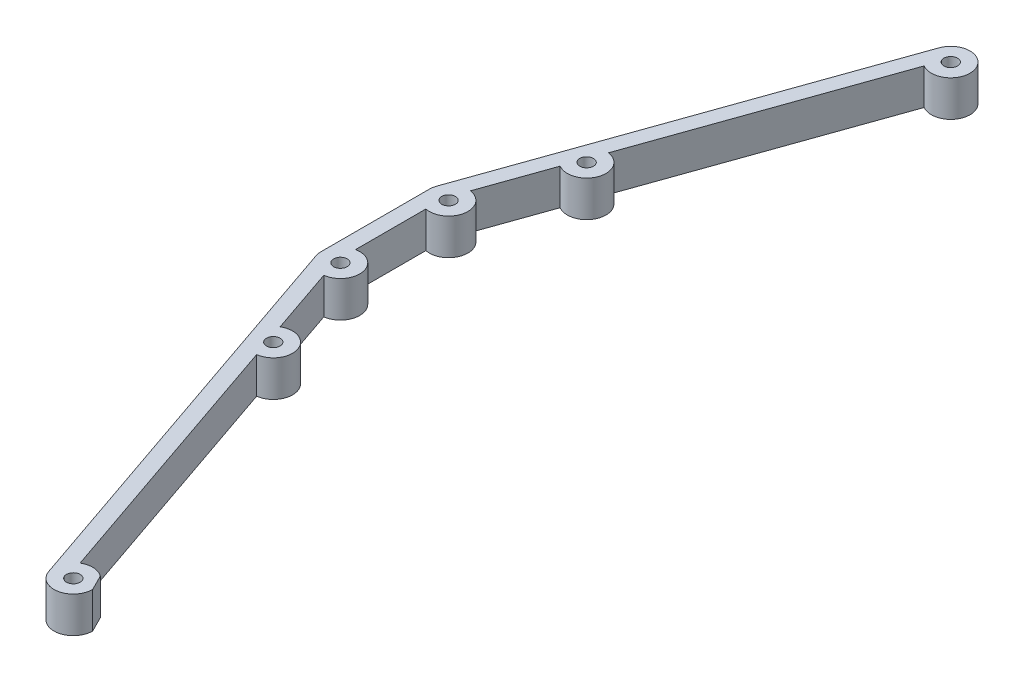
SolidWorks part; units mm, degrees
material "ABS"
ref_plane "Front Plane" through (0, 0, 0) normal (0, 0, 1) x (1, 0, 0)
ref_plane "Top Plane" through (0, 0, 0) normal (0, 1, 0) x (1, 0, 0)
ref_plane "Right Plane" through (0, 0, 0) normal (1, 0, 0) x (0, 0, -1)
sketch "Sketch1" plane through (0, 0, 0) normal (0, 1, 0) x (1, 0, 0)
  line L0 (48.1087, 148.1891) -> (-2.8913, 4.1891)
  line L1 (-3.3216, 1.6852) -> (-3.3216, -40.3148)
  line L2 (-2.9151, -42.7504) -> (51.3349, -200.7504)
  line L3 (18.7854, -87.4758) -> (54.6233, -191.8517)
  line L4 (18.7854, -87.4758) -> (5.1461, -47.7521)
  line L5 (2.6784, -32.9663) -> (2.6784, -5.6633)
  line L6 (5.2177, 9.1128) -> (51.3112, 139.2591)
  line L7 (62.9284, -192.3148) -> (65.9282, -198.264)
  circle A0 centre (55.1784, 145.6852) radius 7.5
  circle A1 centre (18.2, 41.2755) radius 7.5
  circle A2 centre (4.1784, 1.6852) radius 7.5
  circle A3 centre (4.1784, -40.3148) radius 7.5
  circle A4 centre (17.8177, -80.0385) radius 7.5
  circle A5 centre (58.4284, -198.3148) radius 7.5
  circle A6 centre (58.4284, -198.3148) radius 2.65
  circle A7 centre (17.8177, -80.0385) radius 2.65
  circle A8 centre (4.1784, -40.3148) radius 2.65
  circle A9 centre (4.1784, 1.6852) radius 2.65
  circle A10 centre (18.2, 41.2755) radius 2.65
  circle A11 centre (55.1784, 145.6852) radius 2.65
  dimension "D10" = 15
  dimension "D11" = 15
  dimension "D12" = 15
  dimension "D21" = 15
  dimension "D33" = 15
  dimension "D37" = 7.0935
  dimension "D38" = 5.3
  dimension "D39" = 5.3
  dimension "D40" = 5.3
  dimension "D41" = 5.3
  dimension "D42" = 5.3
  dimension "D43" = 5.3
  dimension "D1" = 6
  dimension "D2" = 6
  dimension "D3" = 152.7645
  dimension "D4" = 138.0676
  dimension "D5" = 2.5039
  dimension "D6" = 7.0697
  dimension "D7" = 51
  dimension "D8" = 4.1784
  dimension "D9" = 4.1891
  dimension "D13" = 40.3148
  dimension "D14" = 42
  dimension "D15" = 27.3031
  dimension "D16" = 9.1128
  dimension "D17" = 130.1463
  dimension "D18" = 5.2177
  dimension "D19" = 41.2755
  dimension "D20" = 7.5
  dimension "D22" = 7.5
  dimension "D23" = 6.4261
  dimension "D24" = 1.6852
  dimension "D25" = 3.3216
  dimension "D26" = 2.6784
  dimension "D27" = 7.0935
  dimension "D28" = 2.4356
  dimension "D29" = 158
  dimension "D30" = 167.0541
  dimension "D31" = 42
  dimension "D32" = 1.5
  dimension "D34" = 7.5
  dimension "D35" = 39.7237
  dimension "D36" = 6.4631
  dimension "D44" = 34.6515
  dimension "D45" = 6.6628
  dimension "D46" = 6
extrude "Boss-Extrude2" add sketch "Sketch1" along normal blind 14 contours L7 A5 A6 | A5 L3 A4 L2 | A7 L4 A4 | A7 L4 A4 | A4 L4 A3 L2 | A3 A8 | A3 L5 A2 L1 | A2 A9 | A2 L6 A1 L0 | A10 L6 A1 | A10 L6 A1 | A1 L6 A0 L0 | A0 A11
